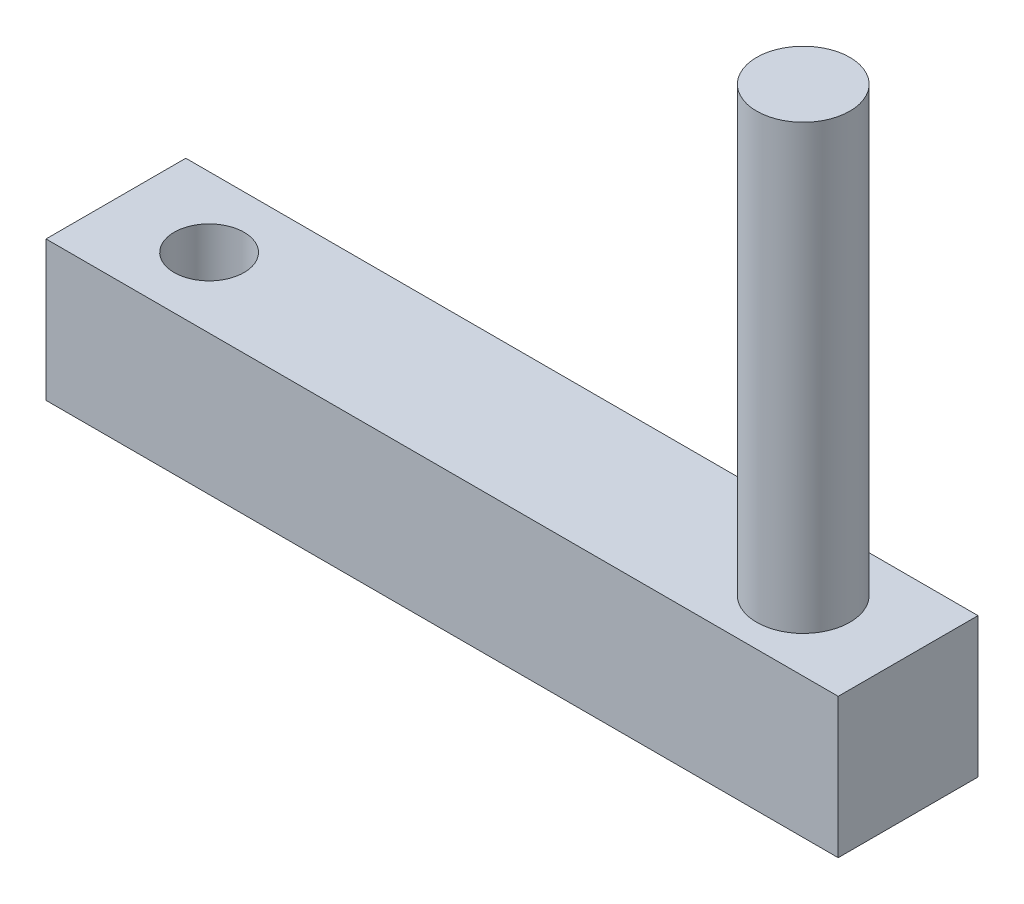
SolidWorks part; units mm, degrees
ref_plane "Front" through (0, 0, 0) normal (0, 0, 1) x (1, 0, 0)
ref_plane "Top" through (0, 0, 0) normal (0, 1, 0) x (1, 0, 0)
ref_plane "Right" through (0, 0, 0) normal (1, 0, 0) x (0, 0, -1)
sketch "Croquis1" plane through (0, 0, 0) normal (0, 1, 0) x (1, 0, 0)
  line L0 (-1000, 0) -> (49000, 0) construction
  line L1 (-8.5, -1.5) -> (8.5, -1.5)
  line L2 (-8.5, -1.5) -> (-8.5, 1.5)
  line L3 (-8.5, 1.5) -> (8.5, 1.5)
  line L4 (8.5, -1.5) -> (8.5, 1.5)
  line L5 (-8.5, -1.5) -> (8.5, 1.5) construction
  line L6 (-8.5, 1.5) -> (8.5, -1.5) construction
  circle A0 centre (-6.5, 0) radius 0.75
  point P0 (0, 0)
  dimension "D3" = 1.5
  dimension "D4" = 2
  dimension "D1" = 3
  dimension "D2" = 17
extrude "Saliente-Extruir1" add sketch "Croquis1" along normal blind 3
sketch "Croquis2" plane through (0, 3, 0) normal (0, 1, 0) x (1, 0, 0)
  line L0 (-1000, 0) -> (49000, 0) construction
  line L1 (8.5, -1.5) -> (8.5, 1.5) construction
  circle A0 centre (6.25, 0) radius 1
  dimension "D1" = 2
  dimension "D2" = 2.25
extrude "Saliente-Extruir2" add sketch "Croquis2" along normal blind 9.5
